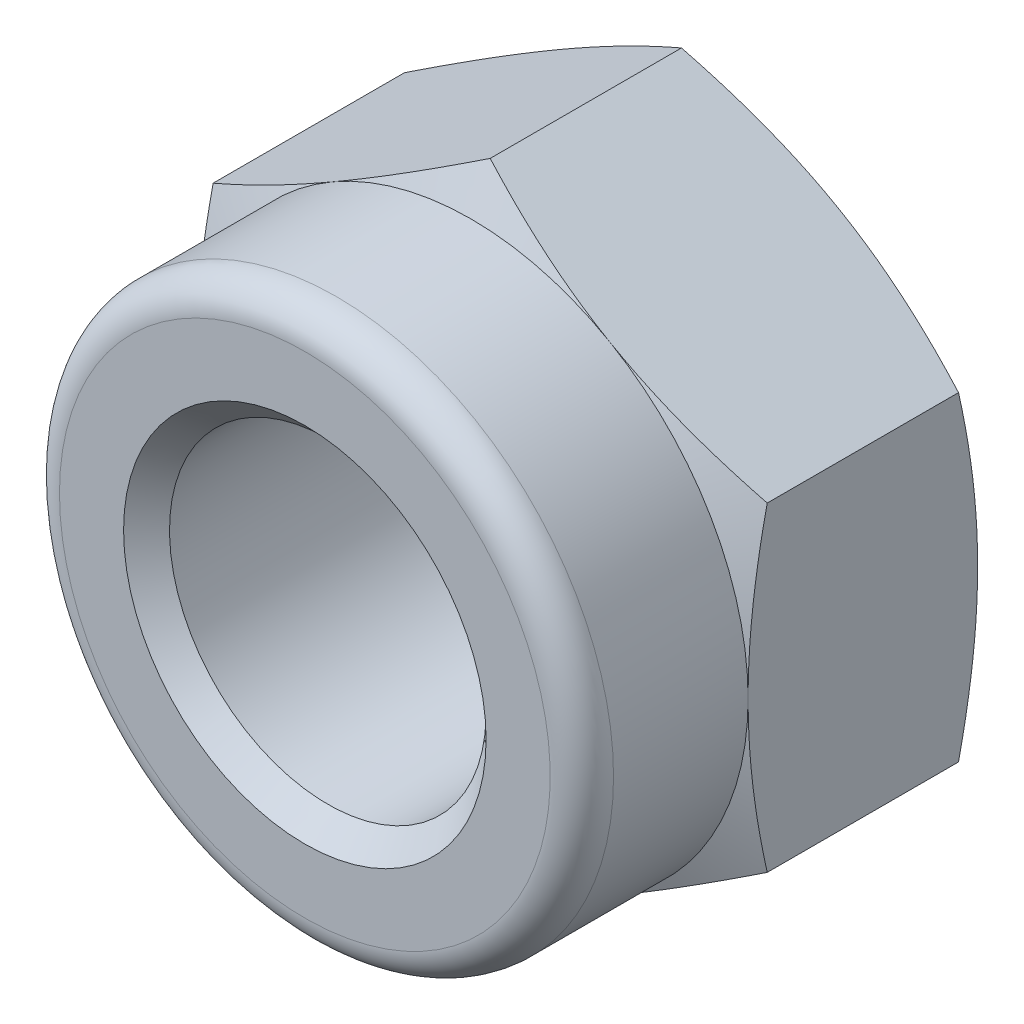
SolidWorks part; units mm, degrees
material "Plain Carbon Steel"
ref_plane "Front Plane" through (0, 0, 0) normal (0, 0, 1) x (1, 0, 0)
ref_plane "Top Plane" through (0, 0, 0) normal (0, 1, 0) x (1, 0, 0)
ref_plane "Right Plane" through (0, 0, 0) normal (1, 0, 0) x (0, 0, -1)
sketch "Sketch1" plane through (0, 0, 0) normal (0, 0, 1) x (1, 0, 0)
  line L1 (0, -4.0415) -> (3.5, -2.0207)
  line L2 (3.5, -2.0207) -> (3.5, 2.0207)
  line L3 (3.5, 2.0207) -> (0, 4.0415)
  line L4 (0, 4.0415) -> (-3.5, 2.0207)
  line L5 (-3.5, 2.0207) -> (-3.5, -2.0207)
  line L6 (-3.5, -2.0207) -> (0, -4.0415)
  circle A0 centre (0, 0) radius 3.5 construction
  circle A1 centre (0, 0) radius 2
  dimension "D2" = 4
  dimension "D1" = 7
extrude "Boss-Extrude1" add sketch "Sketch1" along normal blind 2.9
sketch "Sketch3" plane through (0, 0, 0) normal (0, 1, 0) x (0, 0, -1)
  line L0 (-2.9, 3.5) -> (-4.6, 3.5)
  line L1 (-2.9, -3.5) -> (-2.9, 0) construction
  line L2 (-5, 3.1) -> (-5, 2)
  line L3 (-5, 2) -> (-2.9, 2)
  line L5 (-2.9, 2) -> (-2.9, 3.5)
  line L6 (0, 0) -> (-2.4, 0) construction
  arc A0 (-4.6, 3.5) -> (-5, 3.1) centre (-4.6, 3.1) ccw
  dimension "D1" = 0.4
  dimension "D2" = 5
revolve "Revolve1" add sketch "Sketch3" angle 360 about L6
sketch "Sketch2" plane through (0, 0, 0) normal (1, 0, 0) x (0, 0, -1)
  line L0 (-2.9, 4.0415) -> (-2.9, 3.5)
  line L1 (-2.9, 2.0207) -> (-2.9, 3.0311) construction
  line L2 (-2.9, 3.5) -> (-2.6583, 4.0415)
  line L3 (-2.9, 4.0415) -> (0, 4.0415) construction
  line L4 (-2.6583, 4.0415) -> (-2.9, 4.0415)
  line L5 (-0.2417, 4.0415) -> (0, 4.0415)
  line L6 (0, 4.0415) -> (0, 3.5)
  line L7 (0, 2.0207) -> (0, 4.0415) construction
  line L8 (0, 3.5) -> (-0.2417, 4.0415)
  line L9 (-2.6583, 4.0415) -> (-2.4167, 4.0415) construction
  line L10 (-2.4167, 4.0415) -> (-2.175, 4.0415) construction
  line L11 (-2.175, 4.0415) -> (-1.9333, 4.0415) construction
  line L12 (-1.9333, 4.0415) -> (-1.6917, 4.0415) construction
  line L13 (-1.6917, 4.0415) -> (-1.45, 4.0415) construction
  line L14 (-1.45, 4.0415) -> (-1.2083, 4.0415) construction
  line L15 (-1.2083, 4.0415) -> (-0.9667, 4.0415) construction
  line L16 (-0.9667, 4.0415) -> (-0.725, 4.0415) construction
  line L17 (-0.725, 4.0415) -> (-0.4833, 4.0415) construction
  line L18 (0, 0) -> (-2.4, 0) construction
  line L20 (-5, 2) -> (-4.71, 2)
  line L21 (-4.71, 2) -> (-5, 2.29)
  line L22 (-5, 2.29) -> (-5, 2)
  line L23 (0, 2) -> (-0.29, 2)
  line L24 (0, -2.0207) -> (0, 2.0207) construction
  line L25 (-0.29, 2) -> (0, 2.29)
  line L26 (0, 2.29) -> (0, 2)
  line L27 (-5, 3.1) -> (-5, -3.1) construction
  line L28 (-2.32, 2) -> (-2.61, 2) construction
  line L29 (-2.61, 2) -> (-2.9, 2) construction
  line L30 (-2.32, 2) -> (-2.03, 2) construction
  line L31 (-2.03, 2) -> (-1.74, 2) construction
  line L32 (-1.74, 2) -> (-1.45, 2) construction
  line L33 (-1.45, 2) -> (-1.16, 2) construction
  line L34 (-1.16, 2) -> (-0.87, 2) construction
  line L35 (-0.87, 2) -> (-0.58, 2) construction
  line L36 (-0.58, 2) -> (-0.29, 2) construction
  line L37 (-0.4833, 4.0415) -> (-0.2417, 4.0415) construction
  line L38 (-2.9, 0) -> (-2.9, 2.0207) construction
  dimension "D1" = 7
revolve "Cut-Revolve1" cut sketch "Sketch2" angle 360 about L18
